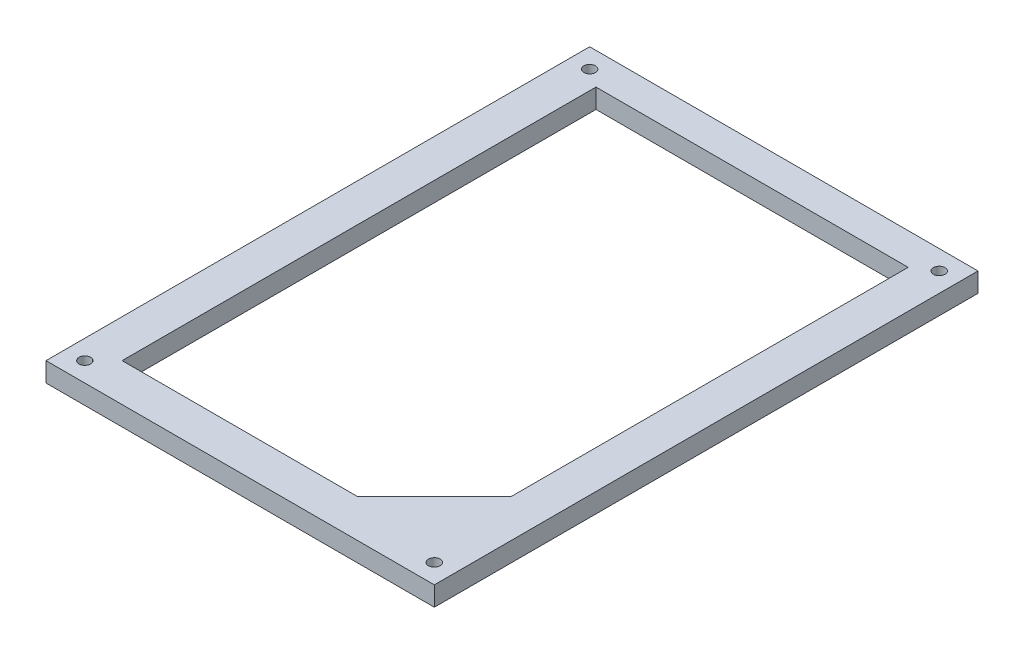
SolidWorks part; units mm, degrees
ref_plane "Front" through (0, 0, 0) normal (0, 0, 1) x (1, 0, 0)
ref_plane "Top" through (0, 0, 0) normal (0, 1, 0) x (1, 0, 0)
ref_plane "Right" through (0, 0, 0) normal (1, 0, 0) x (0, 0, -1)
sketch "Sketch1" plane through (0, 0, 0) normal (0, 1, 0) x (1, 0, 0)
  line L1 (0, 0) -> (127, 0)
  line L2 (0, 0) -> (0, 177.8)
  line L3 (0, 177.8) -> (127, 177.8)
  line L4 (127, 0) -> (127, 177.8)
  dimension "D1" = 127
  dimension "D2" = 177.8
extrude "Boss-Extrude1" add sketch "Sketch1" along normal blind 6.35
sketch "Sketch2" plane through (0, 6.35, 0) normal (0, 1, 0) x (1, 0, 0)
  line L0 (0, 0) -> (127, 0) construction
  line L1 (12.446, 167.4117) -> (114.554, 167.4117)
  line L2 (12.446, 167.4117) -> (12.446, 12.446)
  line L3 (12.446, 12.446) -> (114.554, 12.446)
  line L4 (114.554, 167.4117) -> (114.554, 12.446)
  line L5 (0, 177.8) -> (0, 0) construction
  line L6 (114.554, 37.592) -> (89.408, 12.446)
  dimension "D1" = 102.108
  dimension "D2" = 154.9657
  dimension "D3" = 12.446
  dimension "D4" = 12.446
  dimension "D5" = 25.146
  dimension "D6" = 25.146
extrude "Cut-Extrude1" cut sketch "Sketch2" against normal through all contours L6 L4 L1 L2 L3
sketch "Sketch3" plane through (0, 6.35, 0) normal (0, 1, 0) x (1, 0, 0)
  line L0 (127, 177.8) -> (0, 177.8) construction
  line L1 (0, 177.8) -> (0, 0) construction
  line L2 (63.5, 177.8) -> (63.5, 0) construction
  line L3 (0, 0) -> (127, 0) construction
  line L4 (0, 88.9) -> (127, 88.9) construction
  line L5 (127, 0) -> (127, 177.8) construction
  circle A0 centre (6.35, 171.45) radius 1.905
  circle A1 centre (6.35, 6.35) radius 1.905
  circle A2 centre (120.65, 6.35) radius 1.905
  circle A3 centre (120.65, 171.45) radius 1.905
  dimension "D1" = 3.81
  dimension "D2" = 6.35
  dimension "D3" = 6.35
extrude "Cut-Extrude2" cut sketch "Sketch3" against normal through all
